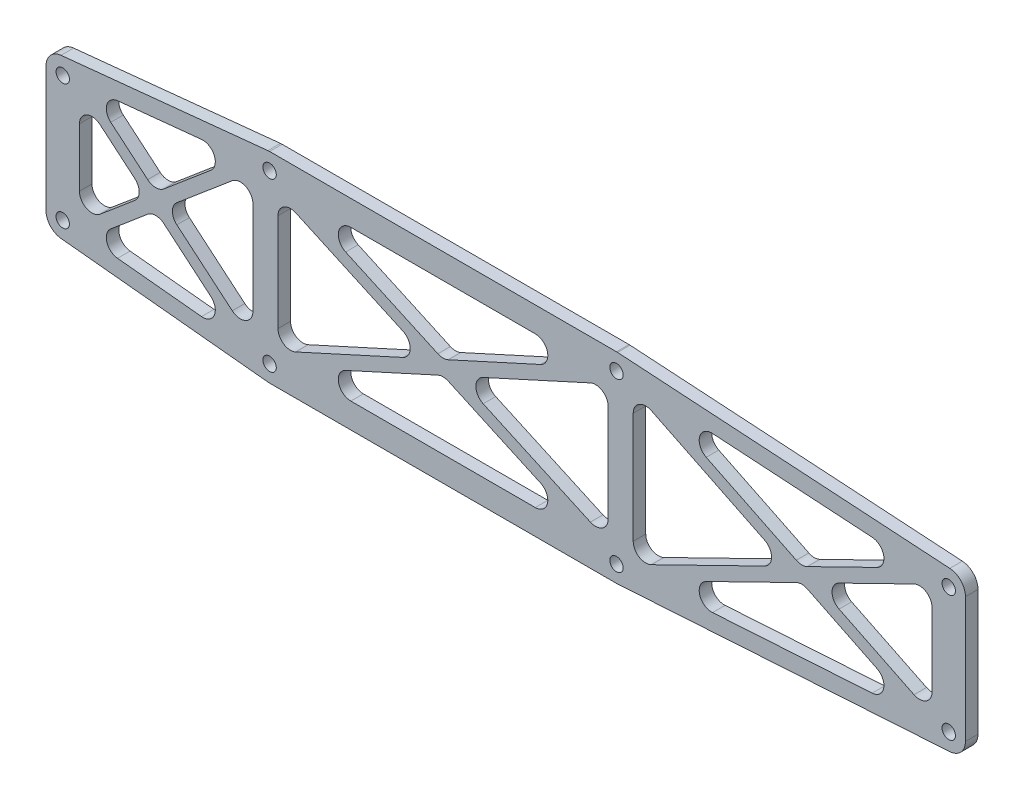
SolidWorks part; units mm, degrees
material "Thornel Mat VMA"
ref_plane "前视基准面" through (0, 0, 0) normal (0, 0, 1) x (1, 0, 0)
ref_plane "上视基准面" through (0, 0, 0) normal (0, 1, 0) x (1, 0, 0)
ref_plane "右视基准面" through (0, 0, 0) normal (1, 0, 0) x (0, 0, -1)
other "Configuration Table"
sketch "草图1" plane through (0, 0, 0) normal (0, 0, 1) x (1, 0, 0)
  line L0 (0, 0) -> (50000, 0) construction
  line L1 (-116, -28) -> (116, -28)
  line L2 (-116, -28) -> (-116, 28)
  line L3 (-116, 28) -> (116, 28)
  line L4 (116, -28) -> (116, 28)
  line L5 (-116, -28) -> (116, 28) construction
  line L6 (-116, 28) -> (116, -28) construction
  line L7 (0, 0) -> (0, -50000) construction
  line L9 (-56.5, -20) -> (26.5, -20) construction
  line L10 (-56.5, -20) -> (-56.5, 20) construction
  line L11 (-56.5, 20) -> (26.5, 20) construction
  line L12 (26.5, -20) -> (26.5, 20) construction
  line L13 (-56.5, -20) -> (26.5, 20) construction
  line L14 (-56.5, 20) -> (26.5, -20) construction
  circle A0 centre (-56.5, 20) radius 1.6
  circle A1 centre (-56.5, -20) radius 1.6
  circle A2 centre (26.5, -20) radius 1.6
  circle A3 centre (26.5, 20) radius 1.6
  point P0 (0, 0)
  point P10 (-15, 0)
  dimension "D3" = 3.2
  dimension "D1" = 232
  dimension "D2" = 56.5
  dimension "D4" = 40
  dimension "D5" = 83
  dimension "D6" = 8
extrude "凸台-拉伸1" add sketch "草图1" along normal blind 3
sketch "草图2" plane through (0, 0, 3) normal (0, 0, 1) x (1, 0, 0)
  line L0 (-106, 28) -> (-106, -28) construction
  line L3 (116, 28) -> (-116, 28) construction
  line L4 (-116, -28) -> (116, -28) construction
  line L5 (0, 0) -> (50000, 0) construction
  line L6 (-116, 28) -> (-116, -28) construction
  line L7 (0, 0) -> (0, -50000) construction
  circle A0 centre (-106, 15) radius 1.6
  circle A1 centre (-106, -15) radius 1.6
  circle A2 centre (106, -15) radius 1.6
  circle A3 centre (106, 15) radius 1.6
  dimension "D2" = 30
  dimension "D3" = 3.2
  dimension "D1" = 56
  dimension "D4" = 10
extrude "切除-拉伸1" cut sketch "草图2" against normal blind 10
sketch "草图4" plane through (0, 0, 3) normal (0, 0, 1) x (1, 0, 0)
  line L0 (110, 15) -> (110, -15)
  line L1 (-110, 15) -> (-110, -15)
  line L2 (-56.5, 24) -> (26.5, 24)
  line L3 (-56.5, -24) -> (26.5, -24)
  line L4 (-106.402, 18.9797) -> (-56.902, 23.9797)
  line L5 (26.7511, 23.9921) -> (106.2511, 18.9921)
  line L6 (26.7511, -23.9921) -> (106.2511, -18.9921)
  line L7 (-106.402, -18.9797) -> (-56.902, -23.9797)
  line L12 (116, -28) -> (116, 28)
  line L13 (116, 28) -> (-116, 28)
  line L14 (-116, 28) -> (-116, -28)
  line L15 (-116, -28) -> (116, -28)
  line L16 (116, -28) -> (116, 28)
  line L17 (116, 28) -> (-116, 28)
  line L18 (-116, 28) -> (-116, -28)
  line L19 (-116, -28) -> (116, -28)
  circle A0 centre (-106, 15) radius 4
  circle A1 centre (-106, -15) radius 4
  circle A2 centre (106, 15) radius 4
  circle A3 centre (106, -15) radius 4
  circle A4 centre (-56.5, 20) radius 4
  circle A5 centre (26.5, 20) radius 4
  circle A6 centre (-56.5, -20) radius 4
  circle A7 centre (26.5, -20) radius 4
  line M18 (116, -28) -> (116, 28)
  line M19 (116, 28) -> (-116, 28)
  line M20 (-116, 28) -> (-116, -28)
  line M21 (-116, -28) -> (116, -28)
  dimension "D1" = 8
  dimension "D2" = 0
extrude "切除-拉伸2" cut sketch "草图4" against normal mid plane 10 contours A7 L3 A6 L7 A1 L1 A0 L4 A4 L2 A5 L5 A2 L0 A3 L6 M21 M18 M19 M20
sketch "草图6" plane through (0, 0, 3) normal (0, 0, 1) x (1, 0, 0)
  line L0 (-54.5, 18) -> (-54.5, -18)
  line L1 (-56.5, 20) -> (26.5, 20) construction
  line L2 (-56.5, 20) -> (-56.5, -20) construction
  line L3 (-56.5, -20) -> (26.5, -20) construction
  line L4 (26.5, 20) -> (26.5, -20) construction
  line L5 (-54.5, -18) -> (24.5, -18)
  line L6 (24.5, 18) -> (24.5, -18)
  line L7 (-54.5, 18) -> (24.5, 18)
  line L8 (-102, 15.404) -> (-102, -15.404)
  line L9 (-102, -15.404) -> (-60.5, -19.596)
  line L10 (-60.5, -19.596) -> (-60.5, 19.596)
  line L11 (-60.5, 19.596) -> (-102, 15.404)
  line L12 (0, 0) -> (50000, 0) construction
  line L13 (-56.902, 23.9797) -> (-106.402, 18.9797) construction
  line L14 (-110, -15) -> (-110, 15) construction
  line L15 (-102, 15.404) -> (-60.5, -19.596) construction
  line L16 (-60.5, 19.596) -> (-102, -15.404) construction
  line L17 (-54.5, 18) -> (24.5, -18) construction
  line L18 (-54.5, -18) -> (24.5, 18) construction
  line L19 (30.5, 19.7484) -> (30.5, -19.7484)
  line L20 (30.5, -19.7484) -> (102, -15.2516)
  line L21 (102, -15.2516) -> (102, 15.2516)
  line L22 (102, 15.2516) -> (30.5, 19.7484)
  line L23 (106.2511, 18.9921) -> (26.7511, 23.9921) construction
  line L24 (110, -15) -> (110, 15) construction
  line L25 (30.5, 19.7484) -> (102, -15.2516) construction
  line L26 (30.5, -19.7484) -> (102, 15.2516) construction
  line L27 (-102.9671, 14.2574) -> (-61.4671, -20.7426)
  line L28 (-61.4671, 20.7426) -> (-102.9671, -14.2574)
  line L29 (-55.122, 16.635) -> (23.878, -19.365)
  line L30 (-53.878, -19.365) -> (25.122, 16.635)
  line L31 (29.8405, 18.4012) -> (101.3405, -16.5988)
  line L32 (31.1595, -21.0957) -> (102.6595, 13.9043)
  line L33 (-101.0329, 16.5507) -> (-59.5329, -18.4493)
  line L34 (-59.5329, 18.4493) -> (-101.0329, -16.5507)
  line L35 (-53.878, 19.365) -> (25.122, -16.635)
  line L36 (-55.122, -16.635) -> (23.878, 19.365)
  line L37 (31.1595, 21.0957) -> (102.6595, -13.9043)
  line L38 (29.8405, -18.4012) -> (101.3405, 16.5988)
  dimension "D1" = 2
  dimension "D2" = 4
  dimension "D3" = 8
  dimension "D4" = 4
  dimension "D5" = 4
  dimension "D6" = 8
  dimension "D7" = 4
  dimension "D8" = 1.5
  dimension "D9" = 1.5
extrude "切除-拉伸3" cut sketch "草图6" against normal mid plane 10 contours L11 L33 L28 | L10 L34 L33 | L27 L34 L9 | L28 L27 L8 | L0 L36 L29 | L35 L36 L7 | L30 L35 L6 | L30 L5 L29 | L19 L38 L31 | L37 L38 L22 | L32 L37 L21 | L32 L20 L31
fillet "圆角1" radius 3 36 edges at (24.5, -16.3516, 1.5) (-11.3827, 0, 1.5) (24.5, 16.3516, 1.5) (20.8827, -18, 1.5) (-50.8827, -18, 1.5) (-15, -1.6484, 1.5) (-99.9222, -15.6139, 1.5) (-83.7352, -1.9622, 1.5) (-63.1432, -19.329, 1.5) (-102, 13.4418, 1.5) (-86.0619, 0, 1.5) (-102, -13.4418, 1.5) (98.9767, -15.4417, 1.5) (34.4147, -19.5022, 1.5) (70.8432, -1.6701, 1.5) (102, -13.5815, 1.5) (74.2549, 0, 1.5) (102, 13.5815, 1.5) (-63.1432, 19.329, 1.5) (-83.7352, 1.9622, 1.5) (-99.9222, 15.6139, 1.5) (34.4147, 19.5022, 1.5) (98.9767, 15.4417, 1.5) (70.8432, 1.6701, 1.5) (-18.6173, 0, 1.5) (-54.5, -16.3516, 1.5) (-60.5, -17.6337, 1.5) (-81.4086, 0, 1.5) (-60.5, 17.6337, 1.5) (30.5, 18.0784, 1.5) (67.4315, 0, 1.5) (30.5, -18.0784, 1.5) (-50.8827, 18, 1.5) (20.8827, 18, 1.5) (-15, 1.6484, 1.5) (-54.5, 16.3516, 1.5)
